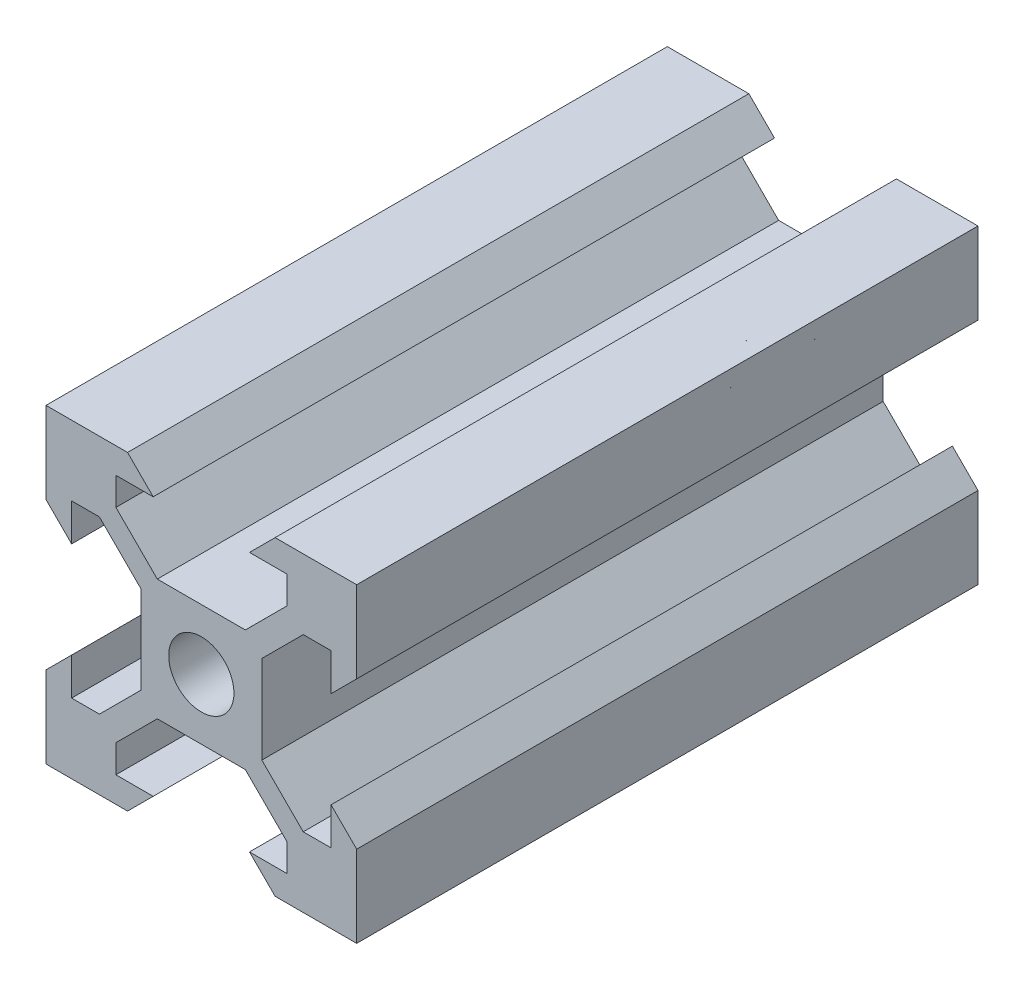
SolidWorks part; units mm, degrees
material "6061-T6 (SS)"
ref_plane "Front Plane" through (0, 0, 0) normal (0, 0, 1) x (1, 0, 0)
ref_plane "Top Plane" through (0, 0, 0) normal (0, 1, 0) x (1, 0, 0)
ref_plane "Right Plane" through (0, 0, 0) normal (1, 0, 0) x (0, 0, -1)
sketch "Sketch1" plane through (0, 0, 0) normal (0, 0, 1) x (1, 0, 0)
  line L0 (2.8343, 3.894) -> (5.5, 6.5588)
  line L1 (2.8343, -3.894) -> (-2.8343, -3.894)
  line L2 (3.8948, -2.8332) -> (3.8948, 2.8332)
  line L3 (2.8343, 3.894) -> (-2.8343, 3.894)
  line L4 (-3.8948, -2.8332) -> (-3.8948, 2.8332)
  line L5 (3.8994, -3.9006) -> (-3.8994, 3.9006) construction
  line L6 (3.9006, 3.8994) -> (-3.9006, -3.8994) construction
  line L7 (10, 4.747) -> (10, 9.9986)
  line L8 (5.5, 6.5588) -> (5.5, 8.3491)
  line L9 (5.5, 8.3491) -> (3.1, 8.3491)
  line L10 (3.1, 8.3491) -> (4.75, 9.9986)
  line L11 (4.75, 9.9986) -> (10, 9.9986)
  line L12 (8.35, 3.0975) -> (10, 4.747)
  line L13 (8.3507, 5.4975) -> (8.35, 3.0975)
  line L14 (6.5605, 5.498) -> (8.3507, 5.4975)
  line L15 (3.8948, 2.8332) -> (6.5605, 5.498)
  line L16 (0, -55) -> (0, 55) construction
  line L17 (-3.8948, 2.8332) -> (-6.5605, 5.498)
  line L18 (-6.5605, 5.498) -> (-8.3507, 5.4975)
  line L19 (-8.3507, 5.4975) -> (-8.35, 3.0975)
  line L20 (-8.35, 3.0975) -> (-10, 4.747)
  line L21 (-4.75, 9.9986) -> (-10, 9.9986)
  line L22 (-3.1, 8.3491) -> (-4.75, 9.9986)
  line L23 (-5.5, 8.3491) -> (-3.1, 8.3491)
  line L24 (-5.5, 6.5588) -> (-5.5, 8.3491)
  line L25 (-10, 4.747) -> (-10, 9.9986)
  line L26 (-2.8343, 3.894) -> (-5.5, 6.5588)
  line L27 (55, 0) -> (-55, 0) construction
  line L28 (3.8948, -2.8332) -> (6.5605, -5.498)
  line L29 (2.8343, -3.894) -> (5.5, -6.5588)
  line L30 (-3.8948, -2.8332) -> (-6.5605, -5.498)
  line L31 (-2.8343, -3.894) -> (-5.5, -6.5588)
  line L32 (-8.3507, -5.4975) -> (-8.35, -3.0975)
  line L33 (-8.35, -3.0975) -> (-10, -4.747)
  line L34 (8.3507, -5.4975) -> (8.35, -3.0975)
  line L35 (8.35, -3.0975) -> (10, -4.747)
  line L36 (-10, -4.747) -> (-10, -9.9986)
  line L37 (-5.5, -6.5588) -> (-5.5, -8.3491)
  line L38 (-5.5, -8.3491) -> (-3.1, -8.3491)
  line L39 (-3.1, -8.3491) -> (-4.75, -9.9986)
  line L40 (-4.75, -9.9986) -> (-10, -9.9986)
  line L41 (-6.5605, -5.498) -> (-8.3507, -5.4975)
  line L42 (6.5605, -5.498) -> (8.3507, -5.4975)
  line L43 (4.75, -9.9986) -> (10, -9.9986)
  line L44 (3.1, -8.3491) -> (4.75, -9.9986)
  line L45 (5.5, -8.3491) -> (3.1, -8.3491)
  line L46 (5.5, -6.5588) -> (5.5, -8.3491)
  line L47 (10, -4.747) -> (10, -9.9986)
  circle A0 centre (0, 0) radius 2.1
  point P0 (0, 0)
  dimension "D6" = 4.2
  dimension "D1" = 7.8
  dimension "D2" = 20
  dimension "D3" = 11
  dimension "D4" = 9.5
  dimension "D5" = 6.2
  dimension "D7" = 1.5
extrude "Boss-Extrude1" add sketch "Sketch1" along normal mid plane 40
